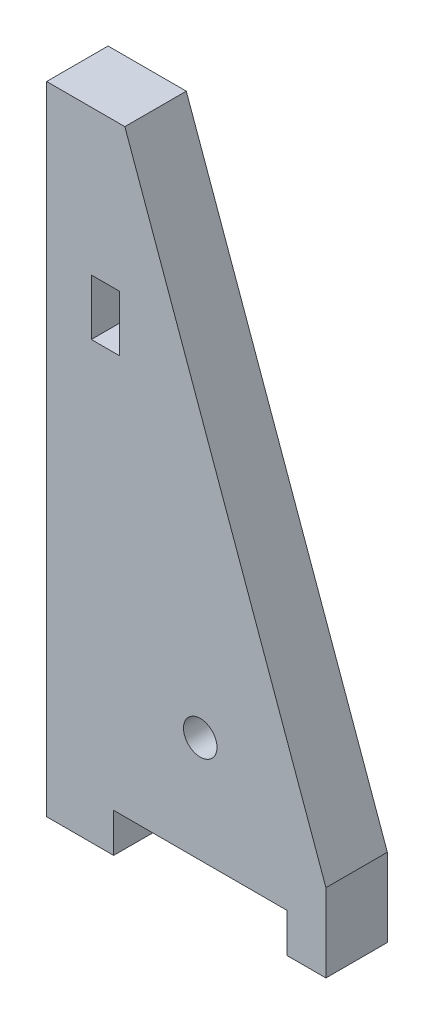
SolidWorks part; units mm, degrees
ref_plane "Alzado" through (0, 0, 0) normal (0, 0, 1) x (1, 0, 0)
ref_plane "Planta" through (0, 0, 0) normal (0, 1, 0) x (1, 0, 0)
ref_plane "Vista lateral" through (0, 0, 0) normal (1, 0, 0) x (0, 0, -1)
sketch "Croquis1" plane through (0, 0, 0) normal (0, 0, 1) x (1, 0, 0)
  line L0 (0, 0) -> (0, -50)
  line L1 (0, -50) -> (25, -50)
  line L2 (25, -50) -> (25, -43)
  line L3 (25, -43) -> (7, -43)
  line L4 (7, -43) -> (7, 0)
  line L5 (7, 0) -> (0, 0)
extrude "Saliente-Extruir1" add sketch "Croquis1" along normal blind 5.5
sketch "Croquis2" plane through (0, 0, 5.5) normal (0, 0, 1) x (1, 0, 0)
  line L0 (25, -43) -> (0, -43)
  line L1 (0, 0) -> (0, -50) construction
  line L2 (0, -43) -> (0, 7)
  line L3 (0, 7) -> (7, 7)
  line L4 (7, 7) -> (25, -43)
extrude "Saliente-Extruir2" add sketch "Croquis2" against normal blind 5.5
sketch "Croquis3" plane through (0, 0, 5.5) normal (0, 0, 1) x (1, 0, 0)
  line L0 (0, -50) -> (25, -50) construction
  line L1 (21.5, -50) -> (6, -50)
  line L2 (21.5, -50) -> (21.5, -46.5)
  line L3 (21.5, -46.5) -> (6, -46.5)
  line L4 (6, -50) -> (6, -46.5)
  line L5 (25, -50) -> (25, -43) construction
  dimension "D1" = 3.5
  dimension "D2" = 15.5
extrude "Cortar-Extruir1" cut sketch "Croquis3" against normal blind 5.5
sketch "Croquis4" plane through (0, 0, 5.5) normal (0, 0, 1) x (1, 0, 0)
  line L0 (0, -50) -> (6, -50) construction
  line L1 (21.5, -46.5) -> (6, -46.5) construction
  circle A0 centre (13.75, -37) radius 1.5
  point P6 (13.75, -46.5)
  dimension "D1" = 13
  dimension "D2" = 0
extrude "Cortar-Extruir2" cut sketch "Croquis4" against normal blind 5.5
sketch "Croquis5" plane through (0, 0, 5.5) normal (0, 0, 1) x (1, 0, 0)
  line L0 (0, 7) -> (0, -50) construction
  line L1 (4, -6) -> (6.5, -6)
  line L2 (4, -6) -> (4, -11)
  line L3 (4, -11) -> (6.5, -11)
  line L4 (6.5, -6) -> (6.5, -11)
  line L5 (7, 7) -> (0, 7) construction
  dimension "D1" = 5
  dimension "D2" = 2.5
  dimension "D3" = 4
  dimension "D4" = 13
extrude "Cortar-Extruir3" cut sketch "Croquis5" against normal blind 10
